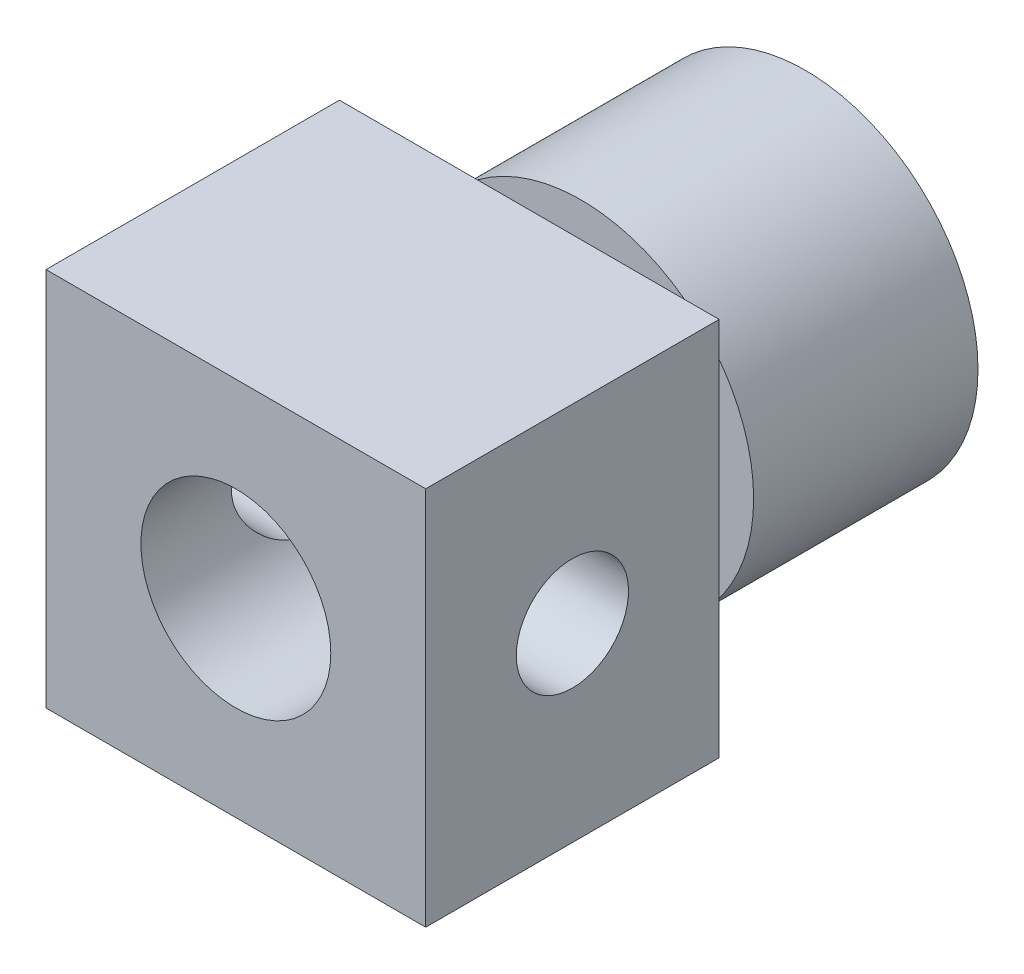
SolidWorks part; units mm, degrees
ref_plane "Front Plane" through (0, 0, 0) normal (0, 0, 1) x (1, 0, 0)
ref_plane "Top Plane" through (0, 0, 0) normal (0, 1, 0) x (1, 0, 0)
ref_plane "Right Plane" through (0, 0, 0) normal (1, 0, 0) x (0, 0, -1)
sketch "Sketch1" plane through (0, 0, 0) normal (0, 0, 1) x (1, 0, 0)
  line L1 (11, 11) -> (-11, 11)
  line L2 (-11, 11) -> (-11, -11)
  line L3 (-11, -11) -> (11, -11)
  line L4 (11, -11) -> (11, 11)
  circle A0 centre (0, 0) radius 11 construction
  dimension "D1" = 22
extrude "Boss-Extrude1" add sketch "Sketch1" along normal blind 17
sketch "Sketch5" plane through (0, 0, 0) normal (0, 0, 1) x (1, 0, 0)
  circle A0 centre (0, 0) radius 7
  dimension "D1" = 14
extrude "Boss-Extrude4" add sketch "Sketch5" against normal blind 3
sketch "Sketch6" plane through (0, 0, -3) normal (0, 0, -1) x (-1, 0, 0)
  circle A0 centre (0, 0) radius 10
  dimension "D1" = 20
extrude "Boss-Extrude5" add sketch "Sketch6" along normal blind 13
sketch "Sketch7" plane through (0, 0, 17) normal (0, 0, 1) x (1, 0, 0)
  circle A0 centre (0, 0) radius 5.5
  dimension "D1" = 11
extrude "Cut-Extrude1" cut sketch "Sketch7" against normal through all
sketch "Sketch8" plane through (11, 0, 0) normal (1, 0, 0) x (0, 0, -1)
  line L0 (-17, -11) -> (-17, 11) construction
  circle A0 centre (-8.5, 0) radius 3.25
  dimension "D1" = 6.5
  dimension "D2" = 8.5
extrude "Cut-Extrude2" cut sketch "Sketch8" against normal mid plane 93
